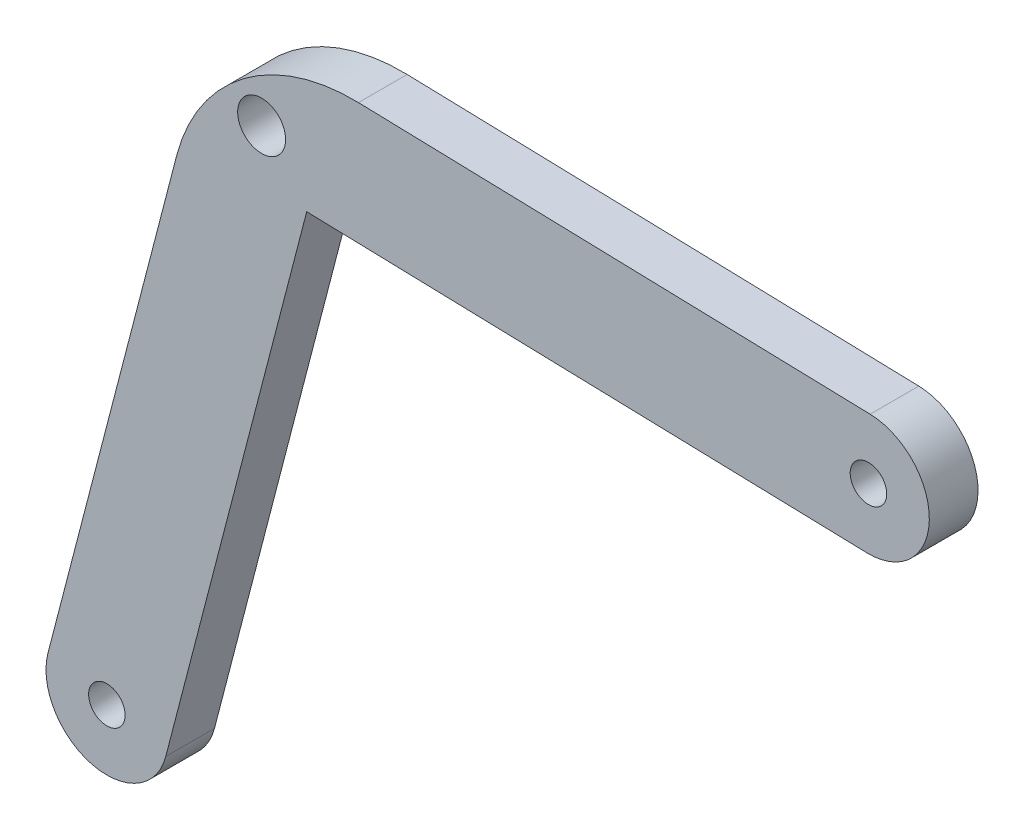
SolidWorks part; units mm, degrees
ref_plane "Plan de face" through (0, 0, 0) normal (0, 0, 1) x (1, 0, 0)
ref_plane "Plan de dessus" through (0, 0, 0) normal (0, 1, 0) x (1, 0, 0)
ref_plane "Plan de droite" through (0, 0, 0) normal (1, 0, 0) x (0, 0, -1)
sketch "Esquisse1" plane through (0, 0, 0) normal (0, 0, 1) x (1, 0, 0)
  line L2 (55.517, 17.4778) -> (1.56, 18.9563)
  line L3 (1.56, 18.9563) -> (-12.0182, -33.2852)
  line L4 (55.2431, 7.4816) -> (9.2375, 8.7422)
  line L5 (9.2375, 8.7422) -> (-2.3398, -35.8007)
  circle A0 centre (5.535, 13.0037) radius 1.9704
  arc A3 (-2.3398, -35.8007) -> (-12.0182, -33.2852) centre (-7.179, -34.5429) cw
  arc A4 (55.2431, 7.4816) -> (55.517, 17.4778) centre (55.38, 12.4797) ccw
  circle A5 centre (-7.179, -34.5429) radius 1.5
  circle A6 centre (55.38, 12.4797) radius 1.5
  dimension "D1" = 3
  dimension "D2" = 3
extrude "Boss.-Extru.1" add sketch "Esquisse1" along normal blind 4
fillet "Congé1" radius 15 1 edges at (1.56, 18.9563, 2)
